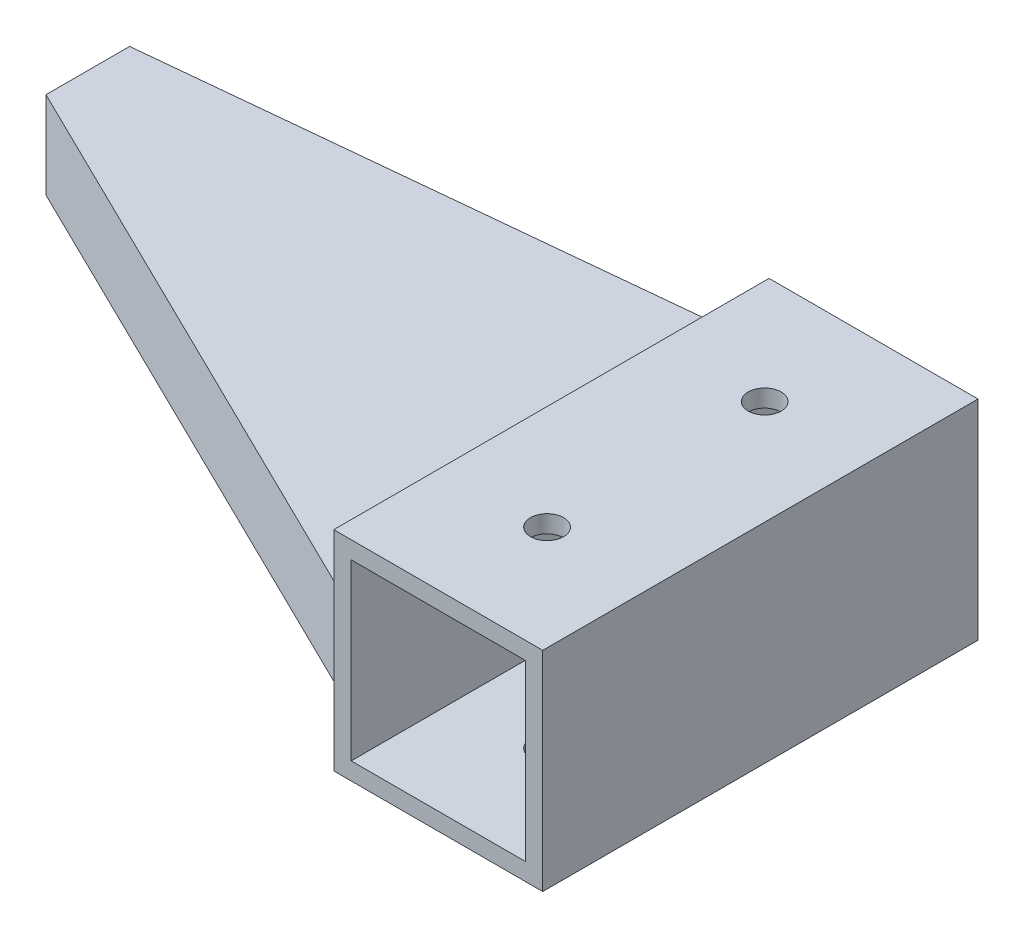
SolidWorks part; units mm, degrees
ref_plane "Front Plane" through (0, 0, 0) normal (0, 0, 1) x (1, 0, 0)
ref_plane "Top Plane" through (0, 0, 0) normal (0, 1, 0) x (1, 0, 0)
ref_plane "Right Plane" through (0, 0, 0) normal (1, 0, 0) x (0, 0, -1)
sketch "Sketch1" plane through (0, 0, 0) normal (0, 1, 0) x (1, 0, 0)
  line L0 (-87.376, 0) -> (0, 0)
  line L1 (0, 0) -> (0, -63.5)
  line L2 (0, -63.5) -> (-87.376, -20.644)
  line L3 (-87.376, -20.644) -> (-87.376, 0)
  dimension "D1" = 87.376
  dimension "D2" = 63.5
  dimension "D3" = 20.644
extrude "Boss-Extrude1" add sketch "Sketch1" along normal blind 12.7
sketch "Sketch2" plane through (-87.376, 0, 0) normal (-1, 0, 0) x (0, 0, 1)
  line L0 (0, 12.7) -> (0, 0) construction
  line L1 (14.548, 6.35) -> (14.548, 12.7) construction
  line L2 (0, 12.7) -> (20.644, 12.7) construction
  line L3 (14.548, 6.35) -> (14.548, 0) construction
  line L4 (0, 0) -> (20.644, 0) construction
  circle A0 centre (14.548, 6.35) radius 3.556
  dimension "D1" = 14.548
  dimension "D2" = 7.112
extrude "Cut-Extrude1" cut sketch "Sketch2" against normal blind 2.9972
sketch "Sketch3" plane through (0, 0, 0) normal (0, 0, -1) x (-1, 0, 0)
  line L0 (0, 12.7) -> (0, 0) construction
  line L1 (0, -6.35) -> (-25.4, -6.35)
  line L2 (0, -6.35) -> (0, 19.05)
  line L3 (0, 19.05) -> (-25.4, 19.05)
  line L4 (-25.4, -6.35) -> (-25.4, 19.05)
  line L5 (8.3033, 0) -> (8.3033, 12.7) construction
  line L6 (0, 0) -> (87.376, 0) construction
  line L7 (0, 12.7) -> (87.376, 12.7) construction
  line L8 (-12.7, -6.35) -> (-12.7, 19.05) construction
  line L9 (0, 6.35) -> (-25.4, 6.35) construction
  line L11 (2.54, 21.59) -> (-27.94, 21.59)
  line L12 (2.54, 21.59) -> (2.54, -8.89)
  line L13 (2.54, -8.89) -> (-27.94, -8.89)
  line L14 (-27.94, 21.59) -> (-27.94, -8.89)
  line L15 (2.54, 21.59) -> (-27.94, -8.89) construction
  line L16 (2.54, -8.89) -> (-27.94, 21.59) construction
  point P12 (8.3033, 6.35)
  point P13 (-25.4, 6.35)
  point P18 (-12.7, 6.35)
  dimension "D1" = 25.4
  dimension "D2" = 2.54
  dimension "D3" = 2.54
extrude "Boss-Extrude2" add sketch "Sketch3" against normal up to vertex (63.5 mm away) up to point (0, 0, 63.5)
sketch "Sketch4" plane through (0, 21.59, 0) normal (0, 1, 0) x (1, 0, 0)
  line L0 (12.7, 0) -> (12.7, -63.5) construction
  line L1 (-2.54, 0) -> (27.94, 0) construction
  line L2 (-2.54, -63.5) -> (27.94, -63.5) construction
  circle A0 centre (12.7, -15.875) radius 2.413
  circle A1 centre (12.7, -47.625) radius 2.413
  dimension "D1" = 4.826
  dimension "D2" = 15.875
  dimension "D3" = 15.875
extrude "Cut-Extrude2" cut sketch "Sketch4" against normal up to surface (30.48 mm away) up to face at (12.7, -8.89, 31.75)
sketch "Sketch6" plane through (-87.376, 0, 0) normal (-1, 0, 0) x (0, 0, 1)
  line L0 (14.548, 2.794) -> (14.548, 12.7) construction
  line L1 (0, 12.7) -> (20.644, 12.7) construction
  line L2 (10.992, 6.35) -> (10.992, 12.7) construction
  line L3 (62.2542, 12.7) -> (0, 12.7) construction
  circle A0 centre (14.548, 6.35) radius 3.556 construction
  circle A1 centre (14.548, 6.35) radius 3.556 construction
sketch "Sketch8" plane through (0, 12.7, 0) normal (0, 1, 0) x (1, 0, 0)
  line L0 (-87.376, -8.452) -> (-2.54, 0)
  line L1 (-87.376, 0) -> (-87.376, -20.644) construction
  line L2 (-87.376, -8.452) -> (-87.376, 0)
  line L3 (-87.376, 0) -> (-2.54, 0)
  dimension "D1" = 2.54
extrude "Cut-Extrude3" cut sketch "Sketch8" against normal up to surface (12.7 mm away) up to face at (-44.958, 0, 20.7245)
